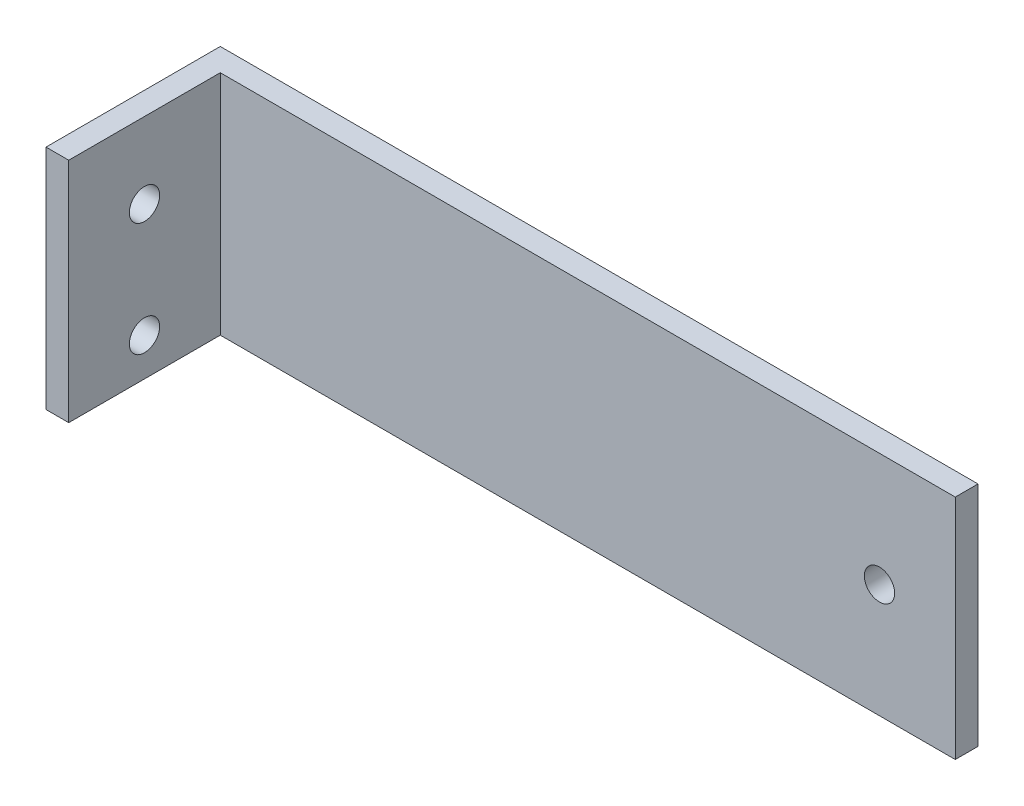
SolidWorks part; units mm, degrees
ref_plane "Front Plane" through (0, 0, 0) normal (0, 0, 1) x (1, 0, 0)
ref_plane "Top Plane" through (0, 0, 0) normal (0, 1, 0) x (1, 0, 0)
ref_plane "Right Plane" through (0, 0, 0) normal (1, 0, 0) x (0, 0, -1)
sketch "Sketch1" plane through (0, 0, 0) normal (0, 0, 1) x (1, 0, 0)
  line L1 (-50, 15) -> (50, 15)
  line L2 (-50, 15) -> (-50, -15)
  line L3 (-50, -15) -> (50, -15)
  line L4 (50, 15) -> (50, -15)
  line L5 (-50, 15) -> (50, -15) construction
  line L6 (-50, -15) -> (50, 15) construction
  point P0 (0, 0)
  dimension "D1" = 100
  dimension "D2" = 30
extrude "Boss-Extrude1" add sketch "Sketch1" along normal blind 3
sketch "Sketch2" plane through (0, 0, 3) normal (0, 0, 1) x (1, 0, 0)
  line L0 (-50, -15) -> (50, -15) construction
  line L1 (-50, 15) -> (-47, 15)
  line L2 (-50, 15) -> (-50, -15)
  line L3 (-50, -15) -> (-47, -15)
  line L4 (-47, 15) -> (-47, -15)
  dimension "D1" = 3
extrude "Boss-Extrude2" add sketch "Sketch2" along normal blind 20
sketch "Sketch3" plane through (-50, 0, 0) normal (-1, 0, 0) x (0, 0, 1)
  line L0 (23, 15) -> (0, 15) construction
  line L2 (0, 15) -> (0, -15) construction
  circle A0 centre (13, 5) radius 2
  circle A1 centre (13, -10) radius 2
  dimension "D1" = 4
  dimension "D2" = 4
  dimension "D3" = 10
  dimension "D4" = 13
  dimension "D5" = 13
  dimension "D6" = 25
extrude "Cut-Extrude1" cut sketch "Sketch3" against normal through all
sketch "Sketch4" plane through (0, 0, 0) normal (0, 0, -1) x (-1, 0, 0)
  line L0 (-50, -15) -> (-50, 15) construction
  circle A0 centre (-40, 0) radius 2
  dimension "D1" = 4
  dimension "D2" = 10
extrude "Cut-Extrude2" cut sketch "Sketch4" against normal blind 10
